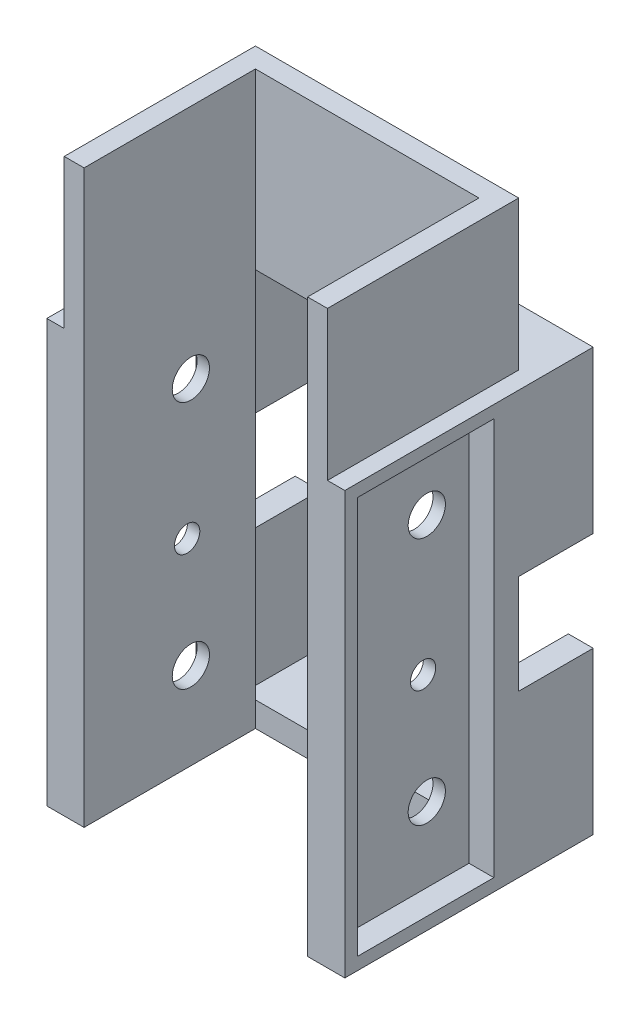
SolidWorks part; units mm, degrees
material "ABS"
ref_plane "Front Plane" through (0, 0, 0) normal (1, 0, 0) x (0, 1, 0)
ref_plane "Top Plane" through (0, 0, 0) normal (0, 0, 1) x (0, 1, 0)
ref_plane "Right Plane" through (0, 0, 0) normal (0, 1, 0) x (-1, 0, 0)
sketch "Sketch1" plane through (0, 0, 0) normal (1, 0, 0) x (0, 1, 0)
  line L9 (-85, 50) -> (85, 50) construction
  line L11 (85, 50) -> (85, -50)
  line L13 (75, 40) -> (75, -50)
  line L15 (-75, 40) -> (-75, -50)
  line L17 (-85, 50) -> (-85, -50)
  line L22 (-85, -50) -> (-75, -50)
  line L28 (75, -50) -> (85, -50)
  line L29 (-85, 50) -> (85, 50)
  line L31 (-75, 40) -> (75, 40)
  line L33 (-85, 0) -> (85, 0) construction
  line L34 (0, 50) -> (0, 0) construction
  dimension "D2" = 75
  dimension "D3" = 10
  dimension "D4" = 10
  dimension "D6" = 100
extrude "Boss-Extrude1" add sketch "Sketch1" along normal mid plane 120
sketch "Sketch3" plane through (60, 0, 0) normal (1, 0, 0) x (0, 1, 0)
  line L6 (-80, 45) -> (-80, -50)
  line L7 (80, 45) -> (-80, 45)
  line L8 (80, -50) -> (80, 45)
  line L11 (-80, 45) -> (-80, -50)
  line L12 (80, 45) -> (-80, 45)
  line L13 (80, -50) -> (80, 45)
  line L34 (85, 50) -> (-85, 50)
  line L35 (-85, 50) -> (-85, -50)
  line L36 (-85, -50) -> (-75, -50)
  line L37 (-75, -50) -> (-75, 40)
  line L38 (-75, 40) -> (75, 40)
  line L39 (75, 40) -> (75, -50)
  line L40 (75, -50) -> (85, -50)
  line L41 (85, -50) -> (85, 50)
  line L44 (-80, -50) -> (-75, -50)
  line L45 (-75, -50) -> (-75, 40)
  line L46 (-75, 40) -> (75, 40)
  line L47 (75, 40) -> (75, -50)
  line L48 (75, -50) -> (80, -50)
  dimension "D1" = 5
  dimension "D2" = 0
extrude "Cut-Extrude2" cut sketch "Sketch3" against normal blind 10
ref_plane "Plane1" through (0, 0, 0) normal (1, 0, 0) x (0, 1, 0)
mirror "Mirror1" about plane through (0, 0, 0) normal (1, 0, 0) of "Cut-Extrude2"
ref_plane "Plane2" through (0, 0, 0) normal (0, 1, 0) x (-1, 0, 0)
sketch "Sketch4" plane through (0, 0, 50) normal (0, 0, 1) x (1, 0, 0)
  line L0 (60, 85) -> (-60, 85) construction
  circle A0 centre (-35, 0) radius 1.5
  circle A1 centre (35, 0) radius 1.5
  circle A2 centre (-35, 60) radius 1.5
  circle A3 centre (35, 60) radius 1.5
  dimension "D1" = 3
  dimension "D5" = 35
  dimension "D2" = 25
  dimension "D3" = 60
  dimension "D4" = 70
extrude "Cut-Extrude3" cut sketch "Sketch4" against normal through all
sketch "Sketch5" plane through (0, 85, 0) normal (0, 1, 0) x (-1, 0, 0)
  line L0 (-60, 50) -> (60, 50) construction
  line L1 (45, 50) -> (-45, 50)
  line L2 (45, 50) -> (45, -19)
  line L4 (-45, 50) -> (-45, -19)
  line L5 (-45, -19) -> (20, -19)
  line L8 (20, -19) -> (45, -19)
  point P4 (0, 50)
  dimension "D1" = 90
  dimension "D5" = 69
extrude "Cut-Extrude4" cut sketch "Sketch5" against normal through all both and the other way through all
sketch "Sketch6" plane through (0, 75, 0) normal (0, -1, 0) x (1, 0, 0)
  line L1 (-45, -19) -> (-45, 40)
  line L2 (-50, -19) -> (-45, -19)
  line L3 (45, -19) -> (50, -19)
  line L10 (-45, -19) -> (-45, 40)
  line L11 (-50, 40) -> (-50, -50)
  line L12 (-50, -50) -> (50, -50)
  line L13 (50, -50) -> (50, 40)
  line L19 (-50, 40) -> (-50, -19)
  line L21 (50, -19) -> (50, 40)
  line L47 (-45, 40) -> (-50, 40)
  line L51 (-45, 40) -> (-50, 40)
  line L53 (50, 40) -> (45, 40)
  line L55 (50, 40) -> (45, 40)
  line L56 (45, 40) -> (45, -19)
  line L57 (45, 40) -> (45, -19)
  line L58 (45, -19) -> (-45, -19)
  dimension "D1" = 0
extrude "Boss-Extrude2" add sketch "Sketch6" along normal up to surface (150 mm away) up to face at (0, -75, 2.75)
sketch "Sketch7" plane through (-50, 0, 0) normal (-1, 0, 0) x (0, -1, 0)
  line L0 (75, -19) -> (-75, -19) construction
  circle A0 centre (-50, 7) radius 7.5
  circle A1 centre (5, 8.5) radius 5.1
  circle A2 centre (50, 7) radius 7.5
  point P9 (0, 0)
  point P12 (0, 0)
  point P13 (0, 0)
  point P14 (0, 0)
  dimension "D1" = 50
  dimension "D4" = 15
  dimension "D5" = 10.2
  dimension "D2" = 50
  dimension "D3" = 5
  dimension "D6" = 26
  dimension "D7" = 27.5
extrude "Cut-Extrude5" cut sketch "Sketch7" against normal through all
sketch "Sketch9" plane through (0, 85, 0) normal (0, 1, 0) x (-1, 0, 0)
  line L0 (-60, -50) -> (60, -50) construction
  line L1 (-20, -50) -> (20, -50)
  line L2 (-20, -50) -> (-20, -40)
  line L3 (-20, -40) -> (20, -40)
  line L4 (20, -50) -> (20, -40)
  point P6 (0, -40)
  dimension "D1" = 40
  dimension "D2" = 10
extrude "Cut-Extrude6" cut sketch "Sketch9" against normal through all
sketch "Sketch11" plane through (0, -80, 0) normal (0, 1, 0) x (-1, 0, 0)
  line L13 (-60, 45) -> (-60, -50) construction
  line L14 (-60, -10) -> (-50, -10)
  line L15 (-60, -10) -> (-60, -50)
  line L16 (-60, -50) -> (-50, -50)
  line L18 (-50, -10) -> (-50, -50)
  line L19 (50, 45) -> (50, -50) construction
  line L24 (60, -50) -> (50, -50)
  line L25 (60, -50) -> (60, -10)
  line L26 (60, -10) -> (50, -10)
  line L32 (50, -50) -> (50, -10)
  dimension "D1" = 40
  dimension "D2" = 40
extrude "Boss-Extrude6" add sketch "Sketch11" along normal up to surface (160 mm away) up to face at (55, 80, -2.5)
sketch "Sketch13" plane through (-60, 0, 0) normal (-1, 0, 0) x (0, -1, 0)
  line L0 (85, -50) -> (-85, -50) construction
  line L1 (-20, -50) -> (20, -50)
  line L2 (-20, -50) -> (-20, -20)
  line L3 (-20, -20) -> (20, -20)
  line L4 (20, -50) -> (20, -20)
  point P6 (0, -20)
  dimension "D1" = 40
  dimension "D2" = 30
extrude "Cut-Extrude7" cut sketch "Sketch13" against normal through all
sketch "Sketch14" plane through (0, 85, 0) normal (0, 1, 0) x (-1, 0, 0)
  line L0 (45, 50) -> (60, 50) construction
  line L1 (-45, 50) -> (-53, 50)
  line L2 (-45, 50) -> (-45, -19)
  line L3 (-44.5834, -27) -> (-53, -27)
  line L4 (-53, 50) -> (-53, -27)
  line L5 (-44.5834, -27) -> (53, -27)
  line L7 (-45, -19) -> (45, -19)
  line L8 (53, -27) -> (53, -19)
  line L10 (45, -19) -> (45, 50)
  line L11 (45, 50) -> (53, 50)
  line L12 (53, -19) -> (53, 50)
  dimension "D1" = 8
  dimension "D2" = 8
extrude "Boss-Extrude7" add sketch "Sketch14" along normal blind 60
